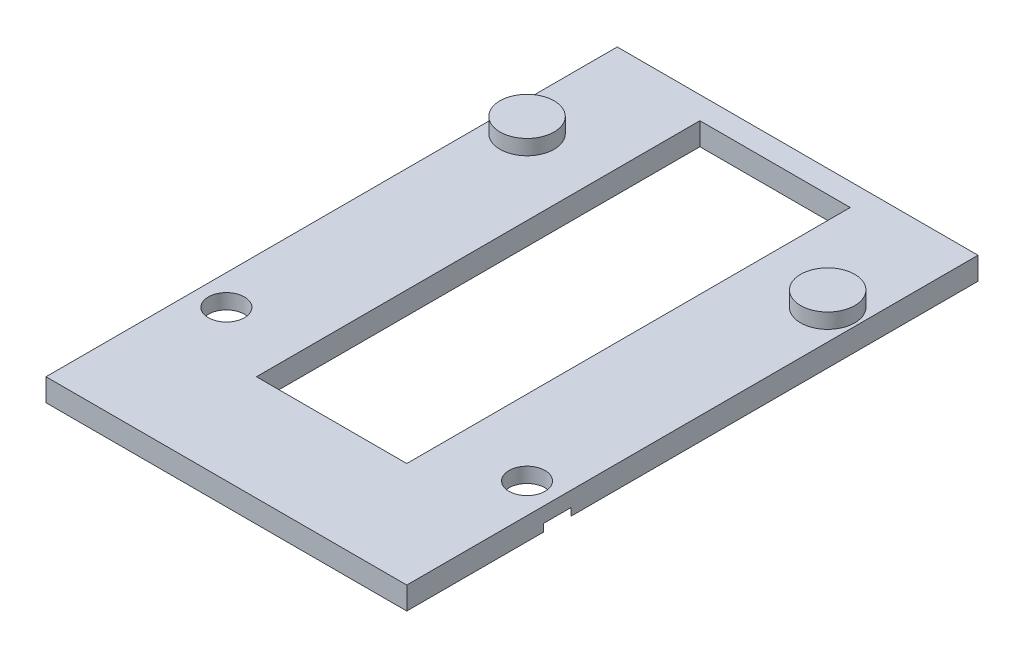
SolidWorks part; units mm, degrees
material "ABS"
ref_plane "Plan de face" through (0, 0, 0) normal (0, 0, 1) x (1, 0, 0)
ref_plane "Plan de dessus" through (0, 0, 0) normal (0, 1, 0) x (1, 0, 0)
ref_plane "Plan de droite" through (0, 0, 0) normal (1, 0, 0) x (0, 0, -1)
sketch "Esquisse1" plane through (0, 0, 0) normal (0, 1, 0) x (1, 0, 0)
  line L1 (-12, -19) -> (12, -19)
  line L2 (-12, -19) -> (-12, 19)
  line L3 (-12, 19) -> (12, 19)
  line L4 (12, -19) -> (12, 19)
  line L5 (-12, -19) -> (12, 19) construction
  line L6 (-12, 19) -> (12, -19) construction
  line L11 (-5, -12) -> (5, -12)
  line L12 (0, 2.75) -> (0, 0) construction
  line L13 (-5, -12) -> (-5, 17.5)
  line L14 (-5, 17.5) -> (5, 17.5)
  line L15 (5, -12) -> (5, 17.5)
  line L16 (-5, -12) -> (5, 17.5) construction
  line L17 (-5, 17.5) -> (5, -12) construction
  point P0 (0, 0)
  dimension "D1" = 24
  dimension "D2" = 38
  dimension "D3" = 1.5
  dimension "D4" = 7
  dimension "D5" = 7
extrude "Shape" add sketch "Esquisse1" along normal blind 1.5
sketch "Esquisse2" plane through (0, 1.5, 0) normal (0, 1, 0) x (1, 0, 0)
  line L0 (10, 19) -> (10, -19) construction
  line L1 (12, 19) -> (-12, 19) construction
  line L2 (-12, -19) -> (12, -19) construction
  line L3 (10, -19) -> (0, -19) construction
  circle A0 centre (10, -9) radius 1.2
  dimension "D2" = 2.4
  dimension "D1" = 10
  dimension "D3" = 10
extrude "VisHoles" cut sketch "Esquisse2" against normal blind 1.5
sketch "Esquisse3" plane through (0, 1.5, 0) normal (0, 1, 0) x (1, 0, 0)
  line L0 (12, 21) -> (-12, 21) construction
  line L1 (12, -19) -> (12, 19) construction
  line L2 (-12, 19) -> (-12, -19) construction
  line L3 (-12, -19) -> (12, -19) construction
  line L4 (0, 21) -> (0, -19) construction
  line L5 (10, -9) -> (10, 1) construction
  line L6 (0, 1) -> (10, 1) construction
  line L7 (10, 1) -> (10, 21) construction
  circle A0 centre (10, 11) radius 1.8
  point P11 (10, 6.4946)
  point P15 (0, 0)
  line M6 (12, -19) -> (12, 19)
  dimension "D2" = 3.6
  dimension "D1" = 40
extrude "Lockers" add sketch "Esquisse3" along normal blind 1 contours A0 M6
sketch "Esquisse4" plane through (0, 0, 0) normal (0, 1, 0) x (1, 0, 0)
  circle A0 centre (10, -9) radius 2.2
  dimension "D1" = 4.4
extrude "ScrewHatRemover" cut sketch "Esquisse4" along normal blind 0.5
mirror "Symétrie1" about plane through (0, 0, 0) normal (1, 0, 0) of "ScrewHatRemover", "VisHoles", "Lockers"
equation "\"entretoiseBearing\"= 1.5mm"
equation "\"length_tibia\"= 206mm"
equation "\"length_femur\"= 117mm"
equation "\"length_coxa\"= 27mm"
equation "\"height\"= 40mm"
equation "\"width\"= 100mm"
equation "\"lever\"= 40mm"
equation "\"errorFlat\"= 0.2mm"
equation "\"errorFlat_tight\"= 0.1mm"
equation "\"errorCircle\"= 0.4mm"
equation "\"errorCircle_tight\" = 0.2mm"
equation "\"cuticule\"=1.5mm"
equation "\"cuticule_attach_w\"=10mm"
equation "\"cuticule_attach_h\"=2.5mm"
equation "\"depthMagnet\"= 1mm"
equation "\"insert_d\" = 3.2mm"
equation "\"insert_l\" = 5mm"
equation "\"D2@Esquisse2\"= 2.00mm + \"errorCircle\""
equation "\"D2@Esquisse3\"= 4 - \"errorCircle\""
equation "\"D1@Esquisse4\"=4 + \"errorCircle\""
